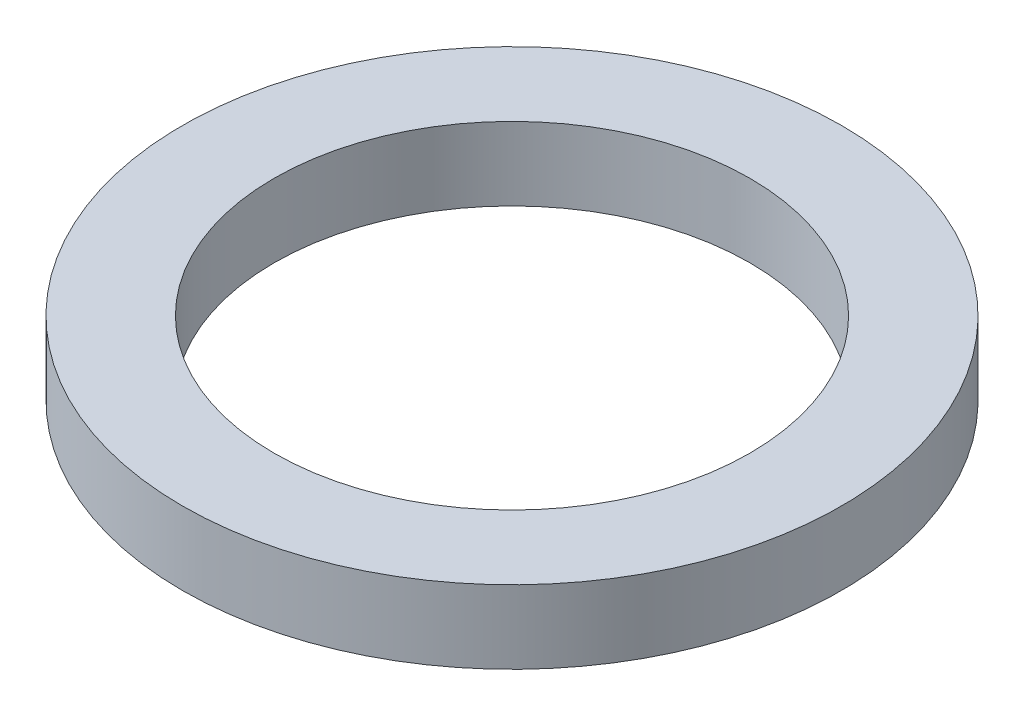
SolidWorks part; units mm, degrees
material "AISI 304"
ref_plane "前视基准面" through (0, 0, 0) normal (0, 0, 1) x (1, 0, 0)
ref_plane "上视基准面" through (0, 0, 0) normal (0, 1, 0) x (1, 0, 0)
ref_plane "右视基准面" through (0, 0, 0) normal (1, 0, 0) x (0, 0, -1)
sketch "草图1" plane through (0, 0, 0) normal (0, 1, 0) x (1, 0, 0)
  circle A0 centre (0, 0) radius 3.25
  circle A1 centre (0, 0) radius 4.5
  dimension "D1" = 6.5
  dimension "D2" = 9
extrude "凸台-拉伸1" add sketch "草图1" along normal blind 1
fillet "圆角1" [suppressed] radius 0.2
other "冻结***"
